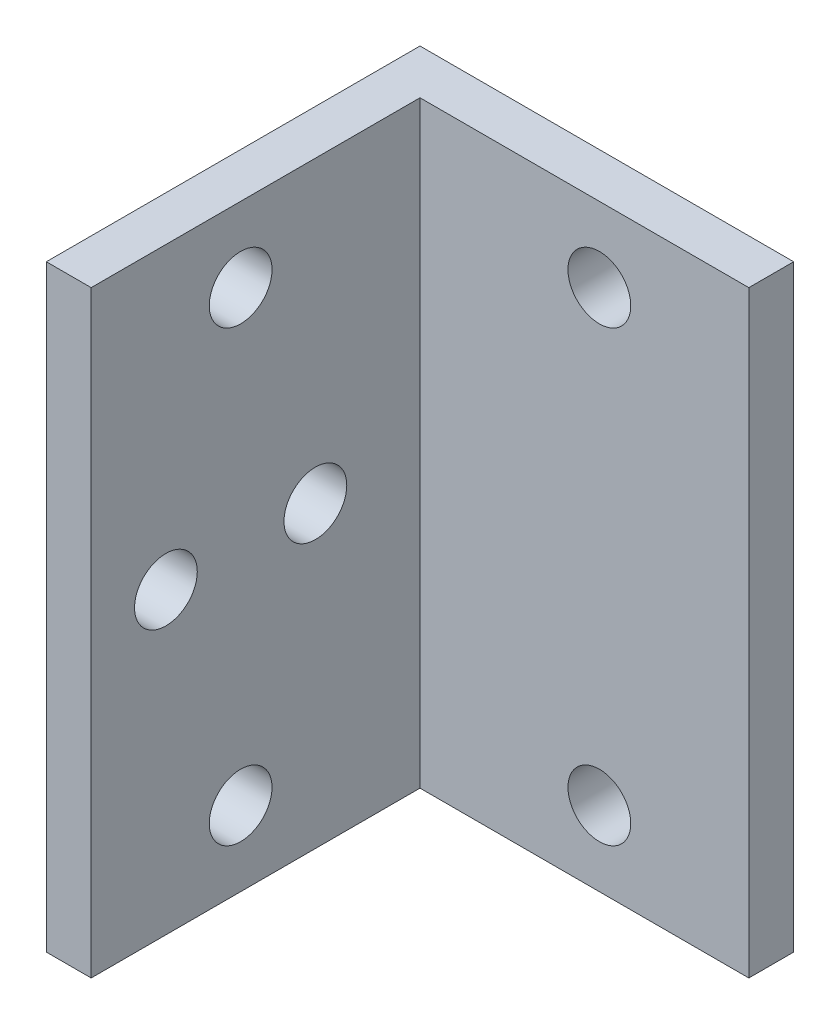
SolidWorks part; units mm, degrees
ref_plane "前视基准面" through (0, 0, 0) normal (0, 0, 1) x (1, 0, 0)
ref_plane "上视基准面" through (0, 0, 0) normal (0, 1, 0) x (1, 0, 0)
ref_plane "右视基准面" through (0, 0, 0) normal (1, 0, 0) x (0, 0, -1)
ref_plane "基准面4" through (0, 0, 20) normal (0, 0, 1) x (1, 0, 0)
sketch "草图1" plane through (0, 0, 20) normal (0, 0, 1) x (1, 0, 0)
  line L0 (33, 220) -> (33, 180)
  line L1 (33, 180) -> (58, 180)
  line L2 (58, 180) -> (58, 220)
  line L3 (58, 220) -> (33, 220)
extrude "凸台-拉伸1" add sketch "草图1" against normal blind 25
sketch "草图2" plane through (0, 220, 0) normal (0, 1, 0) x (-1, 0, 0)
  line L0 (-36, -2) -> (-36, 20)
  line L1 (-36, 20) -> (-58, 20)
  line L2 (-58, 20) -> (-58, -2)
  line L3 (-58, -2) -> (-36, -2)
extrude "切除-拉伸1" cut sketch "草图2" against normal through all
hole_wizard "Ø4.2 (4.2) 直径孔1" positions "草图4" profile "草图3" hole size "Ø4.2" standard "ANSI Metric"
sketch "草图4" plane through (0, 0, -5) normal (0, 0, -1) x (-1, 0, 0)
  point P0 (-48, 185)
  point P1 (-48, 215)
sketch "草图3" plane through (48, 185, -5) normal (1, 0, 0) x (0, 1, 0)
  line L0 (0, 0) -> (0, 25)
  line L1 (0, 25) -> (2.1, 25)
  line L2 (2.1, 25) -> (2.1, 0)
  line L5 (2.1, 0) -> (0, 0)
  line L11 (0, -6.35) -> (0, 107.95) construction
  dimension "通孔孔直径" = 4.2
  dimension "通孔孔深度" = 25
hole_wizard "Ø4.2 (4.2) 直径孔2" positions "草图6" profile "草图5" hole size "Ø4.2" standard "ANSI Metric"
sketch "草图6" plane through (36, 0, 0) normal (1, 0, 0) x (0, 0, -1)
  point P0 (-10, 185)
  point P1 (-10, 215)
  point P2 (-5, 200)
  point P3 (-15, 200)
sketch "草图5" plane through (36, 185, 10) normal (0, 1, 0) x (0, 0, -1)
  line L0 (0, 0) -> (0, 3)
  line L1 (0, 3) -> (2.1, 3)
  line L2 (2.1, 3) -> (2.1, 0)
  line L5 (2.1, 0) -> (0, 0)
  line L11 (0, -6.35) -> (0, 107.95) construction
  dimension "通孔孔直径" = 4.2
  dimension "通孔孔深度" = 3
